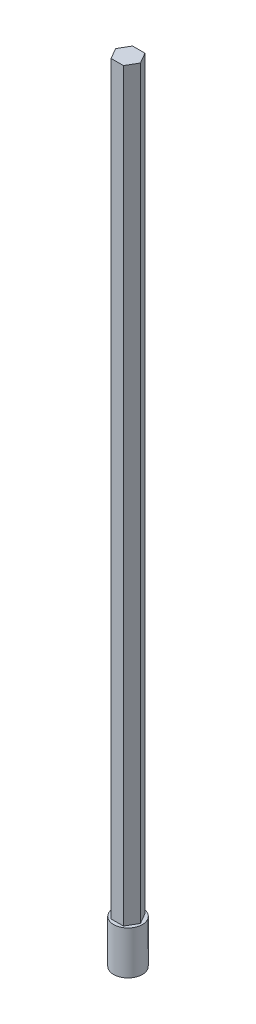
SolidWorks part; units mm, degrees
ref_plane "Alzado" through (0, 0, 0) normal (0, 0, 1) x (1, 0, 0)
ref_plane "Planta" through (0, 0, 0) normal (0, 1, 0) x (1, 0, 0)
ref_plane "Vista lateral" through (0, 0, 0) normal (1, 0, 0) x (0, 0, -1)
sketch "Croquis1" plane through (0, 0, 0) normal (0, 1, 0) x (1, 0, 0)
  line L1 (173.2051, 0) -> (86.6025, 150)
  line L2 (86.6025, 150) -> (-86.6025, 150)
  line L3 (-86.6025, 150) -> (-173.2051, 0)
  line L4 (-173.2051, 0) -> (-86.6025, -150)
  line L5 (-86.6025, -150) -> (86.6025, -150)
  line L6 (86.6025, -150) -> (173.2051, 0)
  circle A0 centre (0, 0) radius 150 construction
  dimension "D1" = 300
extrude "Saliente-Extruir1" add sketch "Croquis1" along normal blind 11000
sketch "Croquis2" plane through (0, 0, 0) normal (0, -1, 0) x (1, 0, 0)
  circle A0 centre (0, 0) radius 200
  dimension "D1" = 400
extrude "Saliente-Extruir2" add sketch "Croquis2" against normal blind 604
